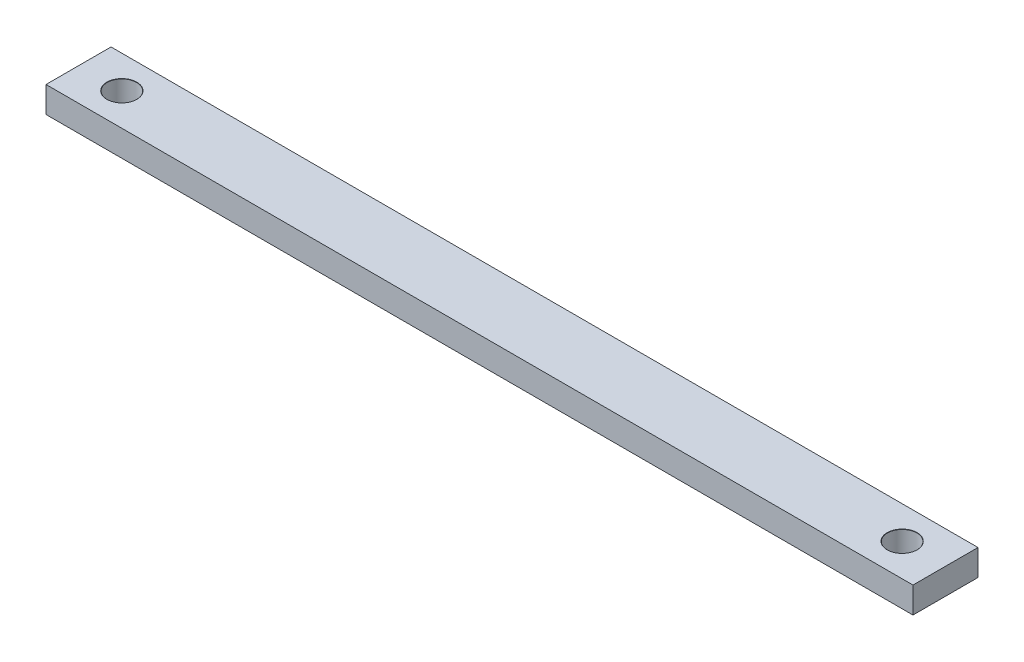
SolidWorks part; units mm, degrees
ref_plane "Front Plane" through (0, 0, 0) normal (0, 0, 1) x (1, 0, 0)
ref_plane "Top Plane" through (0, 0, 0) normal (0, 1, 0) x (1, 0, 0)
ref_plane "Right Plane" through (0, 0, 0) normal (1, 0, 0) x (0, 0, -1)
sketch "Sketch1" plane through (0, 0, 0) normal (0, 1, 0) x (1, 0, 0)
  line L1 (-50, 3.75) -> (50, 3.75)
  line L2 (-50, 3.75) -> (-50, -3.75)
  line L3 (-50, -3.75) -> (50, -3.75)
  line L4 (50, 3.75) -> (50, -3.75)
  line L5 (-50, 3.75) -> (50, -3.75) construction
  line L6 (-50, -3.75) -> (50, 3.75) construction
  point P0 (0, 0)
  dimension "D1" = 100
  dimension "D2" = 7.5
extrude "Boss-Extrude1" add sketch "Sketch1" along normal blind 3
sketch "Sketch4" plane through (0, 3, 0) normal (0, 1, 0) x (1, 0, 0)
  point P0 (-45, 0)
  point P2 (45, 0)
  point P6 (0, 0)
  point P7 (0, 0)
  dimension "D1" = 45
  dimension "D2" = 45
hole_wizard "M3 Clearance Hole1" positions "Sketch4" profile "Sketch3" hole size "M3" standard "ANSI Metric" end condition up to next
sketch "Sketch3" plane through (-45, 3, 0) normal (1, 0, 0) x (0, 0, 1)
  line L0 (0, 0) -> (0, 3)
  line L1 (0, 3) -> (1.7, 3)
  line L2 (1.7, 3) -> (1.7, 0.025)
  line L3 (1.7, 0.025) -> (1.725, 0)
  line L5 (1.725, 0) -> (0, 0)
  line L6 (-1.7, 0.025) -> (-1.725, 0) construction
  line L11 (0, -6.35) -> (0, 107.95) construction
  dimension "Thru Hole Dia." = 3.4
  dimension "Thru Hole Depth" = 3
  dimension "Near C'Sink Dia." = 3.45
  dimension "Near C'Sink Angle" = 90
